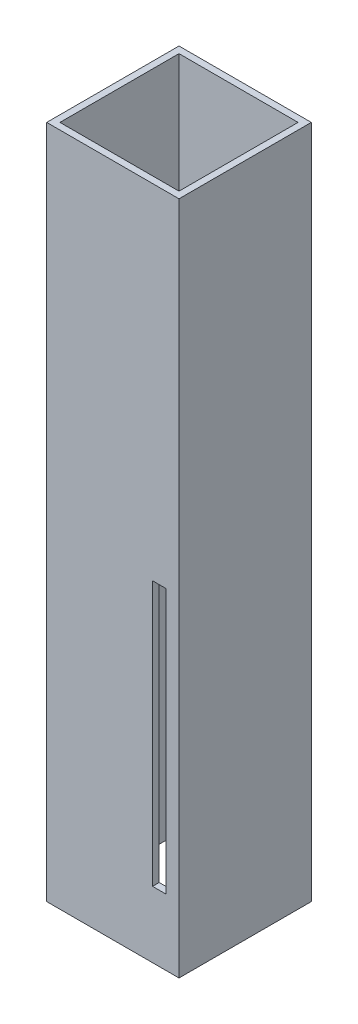
SolidWorks part; units mm, degrees
ref_plane "Front Plane" through (0, 0, 0) normal (0, 0, 1) x (1, 0, 0)
ref_plane "Top Plane" through (0, 0, 0) normal (0, 1, 0) x (1, 0, 0)
ref_plane "Right Plane" through (0, 0, 0) normal (1, 0, 0) x (0, 0, -1)
sketch "Sketch1" plane through (0, 0, 0) normal (0, 1, 0) x (1, 0, 0)
  line L1 (-2.5, -2.5) -> (2.5, -2.5)
  line L2 (-2.5, -2.5) -> (-2.5, 2.5)
  line L3 (-2.5, 2.5) -> (2.5, 2.5)
  line L4 (2.5, -2.5) -> (2.5, 2.5)
  line L5 (-2.5, -2.5) -> (2.5, 2.5) construction
  line L6 (-2.5, 2.5) -> (2.5, -2.5) construction
  line L7 (-2.25, -2.25) -> (2.25, -2.25)
  line L8 (-2.25, -2.25) -> (-2.25, 2.25)
  line L9 (-2.25, 2.25) -> (2.25, 2.25)
  line L10 (2.25, -2.25) -> (2.25, 2.25)
  line L11 (-2.25, -2.25) -> (2.25, 2.25) construction
  line L12 (-2.25, 2.25) -> (2.25, -2.25) construction
  point P0 (0, 0)
  point P6 (0, 0)
  dimension "D1" = 5
  dimension "D2" = 5
  dimension "D3" = 4.5
extrude "Boss-Extrude1" add sketch "Sketch1" along normal blind 25.5
sketch "Sketch2" plane through (0, 0, 2.5) normal (0, 0, 1) x (1, 0, 0)
  line L0 (-2.5, 0) -> (2.5, 0) construction
  line L1 (1.5, 2.5) -> (2, 2.5)
  line L2 (1.5, 2.5) -> (1.5, 12.5)
  line L3 (1.5, 12.5) -> (2, 12.5)
  line L4 (2, 2.5) -> (2, 12.5)
  line L5 (2.5, 25.5) -> (2.5, 0) construction
  dimension "D1" = 0.5
  dimension "D2" = 10
  dimension "D3" = 2.5
  dimension "D4" = 0.5
extrude "Cut-Extrude1" cut sketch "Sketch2" against normal through all both and the other way through all
